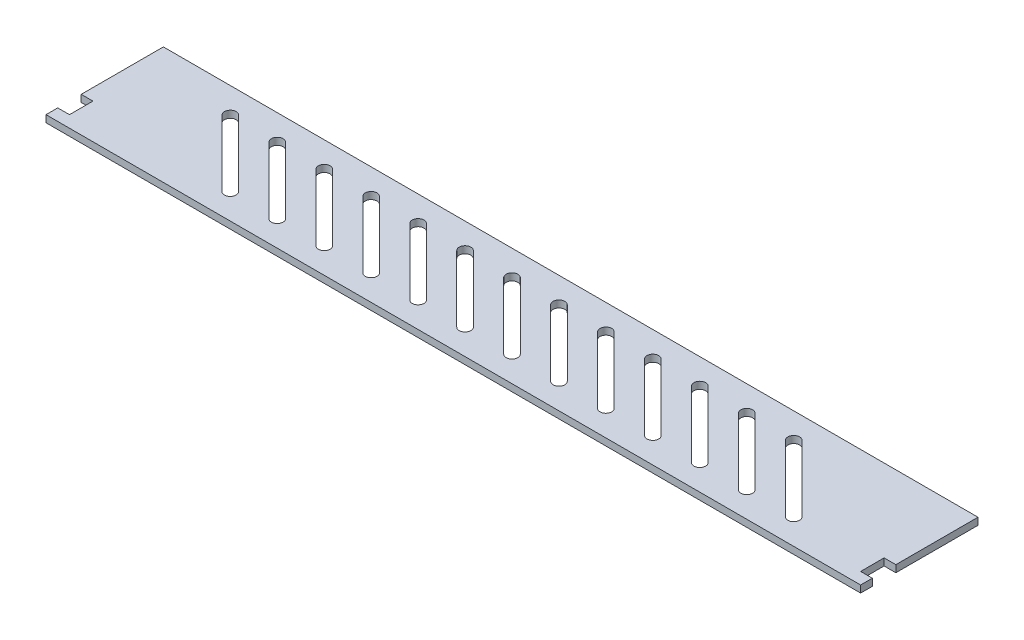
SolidWorks part; units mm, degrees
ref_plane "Front Plane" through (0, 0, 0) normal (0, 0, 1) x (1, 0, 0)
ref_plane "Top Plane" through (0, 0, 0) normal (0, 1, 0) x (1, 0, 0)
ref_plane "Right Plane" through (0, 0, 0) normal (1, 0, 0) x (0, 0, -1)
sketch "Sketch1" plane through (0, 0, 0) normal (0, 1, 0) x (1, 0, 0)
  line L1 (-173.5, -25) -> (173.5, -25)
  line L2 (-173.5, -25) -> (-173.5, 25)
  line L3 (-173.5, 25) -> (173.5, 25)
  line L4 (173.5, -25) -> (173.5, 25)
  line L5 (-173.5, -25) -> (173.5, 25) construction
  line L6 (-173.5, 25) -> (173.5, -25) construction
  point P0 (0, 0)
  dimension "D1" = 347
  dimension "D2" = 50
extrude "Extrude1" add sketch "Sketch1" along normal blind 3
sketch "Sketch2" plane through (0, 3, 0) normal (0, 1, 0) x (1, 0, 0)
  line L0 (0, -25) -> (0, 25) construction
  line L1 (-173.5, -25) -> (173.5, -25) construction
  line L2 (173.5, 25) -> (-173.5, 25) construction
  line L3 (15.9099, -12.3744) -> (-12.3744, 15.9099)
  line L4 (-12.3744, 15.9099) -> (-15.9099, 12.3744) construction
  line L5 (-15.9099, 12.3744) -> (12.3744, -15.9099)
  line L6 (12.3744, -15.9099) -> (15.9099, -12.3744) construction
  line L7 (14.1421, -14.1421) -> (-14.1421, 14.1421) construction
  arc A0 (-15.9099, 12.3744) -> (-12.3744, 15.9099) centre (-14.1421, 14.1421) cw
  arc A1 (12.3744, -15.9099) -> (15.9099, -12.3744) centre (14.1421, -14.1421) ccw
  point P12 (0, 0)
  dimension "D1" = 5
  dimension "D2" = 40
  dimension "D3" = 45
extrude "Extrude2" cut sketch "Sketch2" against normal through all
pattern_linear "LPattern1" count 7 spacing 20 along (1, 0, 0) count 7 spacing 20 along (-1, 0, 0) of "Extrude2"
sketch "Sketch3" plane through (0, 3, 0) normal (0, 1, 0) x (1, 0, 0)
  line L0 (-173.5, 25) -> (-173.5, -25) construction
  line L1 (-173.5, -20) -> (-168.5, -20)
  line L2 (-173.5, -20) -> (-173.5, -10)
  line L3 (-173.5, -10) -> (-168.5, -10)
  line L4 (-168.5, -20) -> (-168.5, -10)
  line L5 (-173.5, -25) -> (173.5, -25) construction
  dimension "D1" = 5
  dimension "D2" = 5
  dimension "D3" = 10
extrude "Extrude3" cut sketch "Sketch3" against normal up to next
mirror "Mirror1" about plane through (0, 0, 0) normal (1, 0, 0) of "Extrude3"
